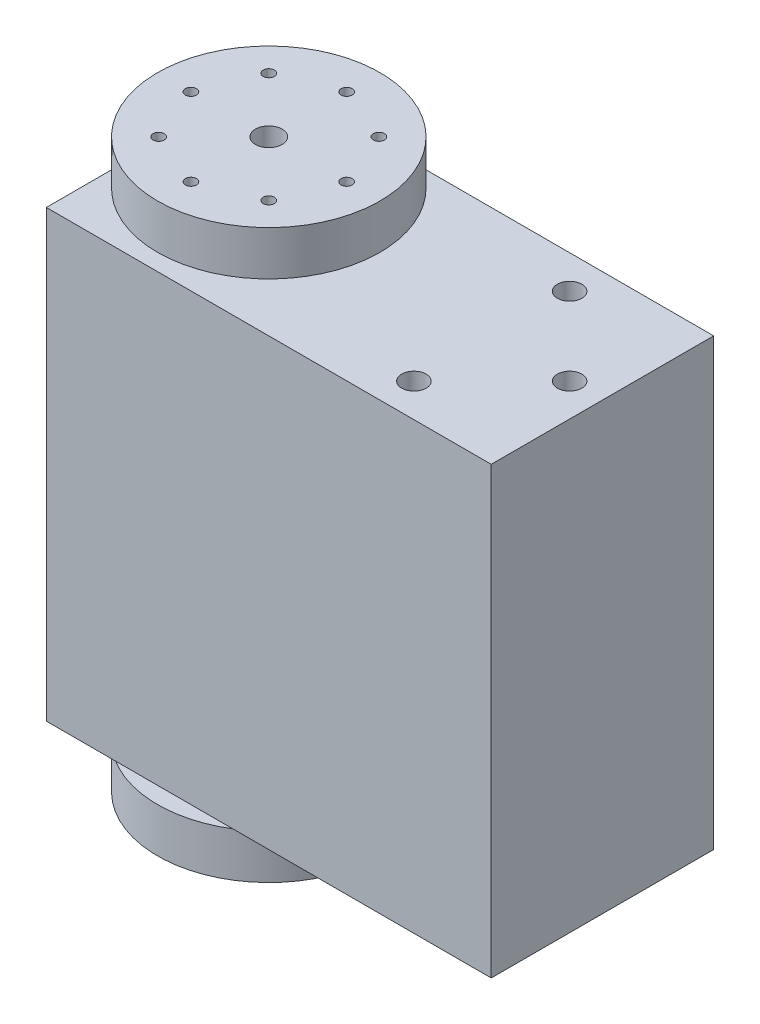
SolidWorks part; units mm, degrees
ref_plane "Front Plane" through (0, 0, 0) normal (0, 0, 1) x (1, 0, 0)
ref_plane "Top Plane" through (0, 0, 0) normal (0, 1, 0) x (1, 0, 0)
ref_plane "Right Plane" through (0, 0, 0) normal (1, 0, 0) x (0, 0, -1)
sketch "Sketch1" plane through (0, 0, 0) normal (0, 1, 0) x (1, 0, 0)
  line L1 (-253.7698, 159.9018) -> (-213.7698, 159.9018)
  line L2 (-253.7698, 159.9018) -> (-253.7698, 139.9018)
  line L3 (-253.7698, 139.9018) -> (-213.7698, 139.9018)
  line L4 (-213.7698, 159.9018) -> (-213.7698, 139.9018)
  line L5 (-253.7698, 159.9018) -> (-213.7698, 139.9018) construction
  line L6 (-253.7698, 139.9018) -> (-213.7698, 159.9018) construction
  point P0 (-233.7698, 149.9018)
  dimension "D1" = 20
  dimension "D2" = 40
extrude "Boss-Extrude1" add sketch "Sketch1" along normal blind 40
sketch "Sketch3" plane through (0, 40, 0) normal (0, 1, 0) x (1, 0, 0)
  line L0 (-213.7698, 159.9018) -> (-253.7698, 159.9018) construction
  line L1 (-253.7698, 159.9018) -> (-253.7698, 139.9018) construction
  circle A0 centre (-243.7698, 149.9018) radius 6.5
  dimension "D1" = 13
  dimension "D2" = 10
  dimension "D3" = 10
extrude "Boss-Extrude2" add sketch "Sketch3" along normal blind 1.5
sketch "Sketch4" plane through (0, 0, 0) normal (0, -1, 0) x (1, 0, 0)
  line L0 (-253.7698, -139.9018) -> (-213.7698, -139.9018) construction
  line L1 (-253.7698, -159.9018) -> (-253.7698, -139.9018) construction
  circle A0 centre (-243.7698, -149.9018) radius 6.5
  dimension "D1" = 13
  dimension "D2" = 10
  dimension "D3" = 10
extrude "Boss-Extrude3" add sketch "Sketch4" along normal blind 1.5
sketch "Sketch5" plane through (0, -1.5, 0) normal (0, -1, 0) x (1, 0, 0)
  circle A0 centre (-243.7698, -149.9018) radius 10
  circle A1 centre (-243.7698, -149.9018) radius 1.15
  dimension "D1" = 20
  dimension "D2" = 2.3
extrude "Boss-Extrude4" add sketch "Sketch5" along normal blind 4
sketch "Sketch6" plane through (0, 41.5, 0) normal (0, 1, 0) x (1, 0, 0)
  circle A0 centre (-243.7698, 149.9018) radius 10
  circle A1 centre (-243.7698, 149.9018) radius 1.2
  dimension "D1" = 20
  dimension "D2" = 2.4
extrude "Boss-Extrude6" add sketch "Sketch6" along normal blind 4
sketch "Sketch8" plane through (-253.7698, 0, 0) normal (-1, 0, 0) x (0, 0, 1)
  line L0 (-149.9018, 42.0829) -> (-149.9018, -3.4849) construction
  line L2 (-153.9018, 12.9713) -> (-145.9018, 12.9713)
  line L3 (-153.9018, 12.9713) -> (-153.9018, 7.9713)
  line L4 (-153.9018, 7.9713) -> (-145.9018, 7.9713)
  line L5 (-145.9018, 12.9713) -> (-145.9018, 7.9713)
  line L6 (-153.9018, 12.9713) -> (-145.9018, 7.9713) construction
  line L7 (-153.9018, 7.9713) -> (-145.9018, 12.9713) construction
  point P2 (-149.9018, 10.4713)
  dimension "D1" = 5
  dimension "D2" = 8
extrude "Cut-Extrude1" cut sketch "Sketch8" against normal blind 3
sketch "Sketch9" plane through (0, 40, 0) normal (0, 1, 0) x (1, 0, 0)
  line L0 (-257.0292, 149.9018) -> (-211.7228, 149.9018) construction
  line L2 (-223.7198, 137.5968) -> (-223.7198, 161.2893) construction
  line L3 (-213.7698, 139.9018) -> (-213.7698, 159.9018) construction
  circle A0 centre (-216.7198, 149.9018) radius 1.1
  circle A1 centre (-223.7198, 142.9018) radius 1.1
  circle A2 centre (-223.7198, 156.9018) radius 1.1
  dimension "D1" = 2.2
  dimension "D2" = 2.2
  dimension "D3" = 2.2
  dimension "D4" = 14
  dimension "D5" = 7
  dimension "D6" = 2.95
extrude "Cut-Extrude2" cut sketch "Sketch9" against normal blind 3
sketch "Sketch10" plane through (0, 0, 0) normal (0, -1, 0) x (1, 0, 0)
  line L0 (-211.6098, -149.9018) -> (-257.7222, -149.9018) construction
  line L1 (-216.2398, -165.9407) -> (-216.2398, -139.3619) construction
  line L2 (-213.7698, -139.9018) -> (-213.7698, -159.9018) construction
  circle A0 centre (-216.2398, -157.4018) radius 1.1
  circle A1 centre (-216.2398, -142.4018) radius 1.1
  circle A2 centre (-231.2398, -157.4018) radius 1.1
  circle A3 centre (-231.2398, -142.4018) radius 1.1
  dimension "D1" = 2.2
  dimension "D2" = 2.2
  dimension "D3" = 15
  dimension "D5" = 2.47
  dimension "D4" = 2
extrude "Cut-Extrude3" cut sketch "Sketch10" against normal blind 3
sketch "Sketch13" plane through (0, -5.5, 0) normal (0, -1, 0) x (1, 0, 0)
  line L1 (-243.7698, -163.0923) -> (-243.7698, -138.741) construction
  circle A0 centre (-243.7698, -142.9018) radius 0.5
  circle A1 centre (-243.7698, -149.9018) radius 10 construction
  circle A2 centre (-238.82, -144.9521) radius 0.5
  circle A3 centre (-236.7698, -149.9018) radius 0.5
  circle A4 centre (-238.82, -154.8516) radius 0.5
  circle A5 centre (-243.7698, -156.9018) radius 0.5
  circle A6 centre (-248.7195, -154.8516) radius 0.5
  circle A7 centre (-250.7698, -149.9018) radius 0.5
  circle A8 centre (-248.7195, -144.9521) radius 0.5
  point P23 (-243.7698, -149.9018)
  dimension "D1" = 1
  dimension "D2" = 7
  dimension "D3" = 8
extrude "Cut-Extrude5" cut sketch "Sketch13" against normal blind 4
sketch "Sketch14" plane through (0, 45.5, 0) normal (0, 1, 0) x (1, 0, 0)
  line L1 (-243.7698, 139.3229) -> (-243.7698, 160.6667) construction
  circle A0 centre (-243.7698, 156.9018) radius 0.5
  circle A1 centre (-243.7698, 149.9018) radius 10 construction
  circle A2 centre (-238.82, 154.8516) radius 0.5
  circle A3 centre (-236.7698, 149.9018) radius 0.5
  circle A4 centre (-238.82, 144.9521) radius 0.5
  circle A5 centre (-243.7698, 142.9018) radius 0.5
  circle A6 centre (-248.7195, 144.9521) radius 0.5
  circle A7 centre (-250.7698, 149.9018) radius 0.5
  circle A8 centre (-248.7195, 154.8516) radius 0.5
  point P24 (-243.7698, 149.9018)
  dimension "D1" = 1
  dimension "D2" = 7
  dimension "D3" = 8
extrude "Cut-Extrude6" cut sketch "Sketch14" against normal blind 4
